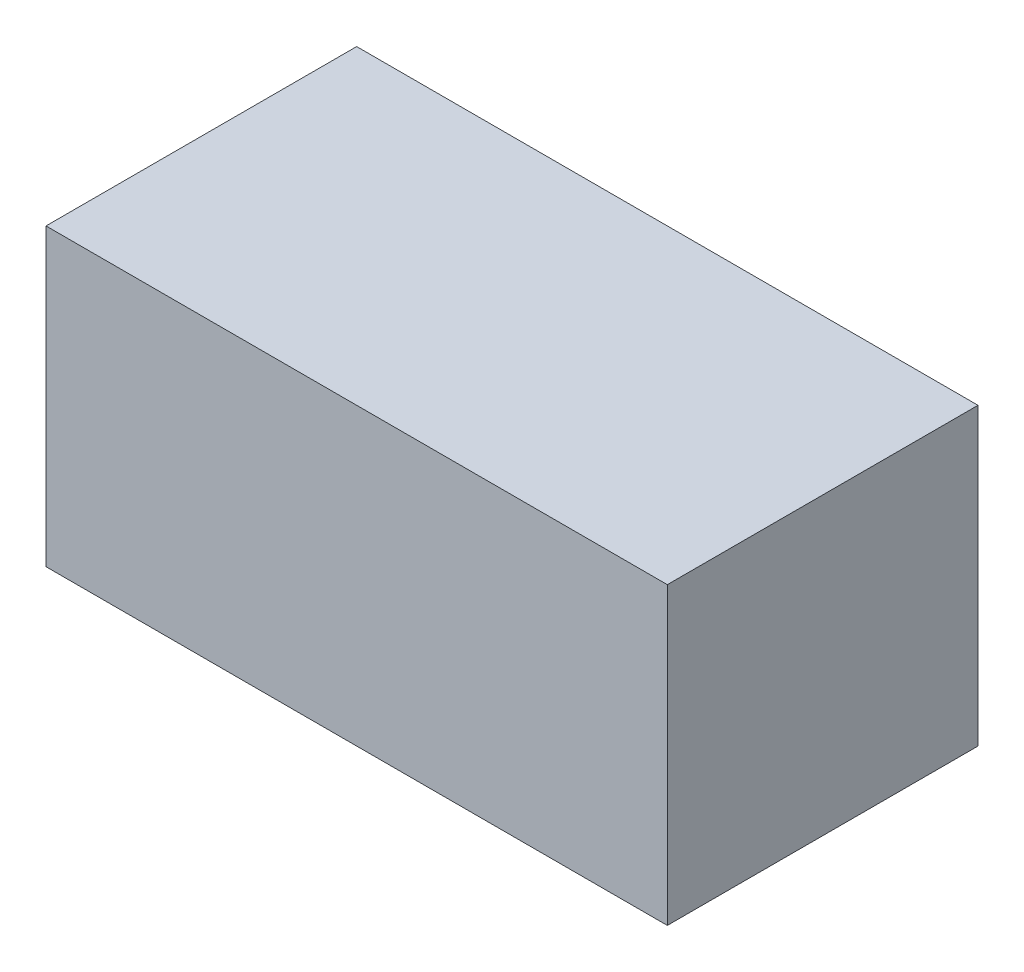
SolidWorks part; units mm, degrees
ref_plane "Front Plane" through (0, 0, 0) normal (0, 0, 1) x (1, 0, 0)
ref_plane "Top Plane" through (0, 0, 0) normal (0, 1, 0) x (1, 0, 0)
ref_plane "Right Plane" through (0, 0, 0) normal (1, 0, 0) x (0, 0, -1)
sketch "Sketch1" plane through (0, 0, 0) normal (0, 1, 0) x (1, 0, 0)
  line L1 (0, 0) -> (40, 0)
  line L2 (0, 0) -> (0, 20)
  line L3 (0, 20) -> (40, 20)
  line L4 (40, 0) -> (40, 20)
extrude "Boss-Extrude1" add sketch "Sketch1" against normal blind 19
